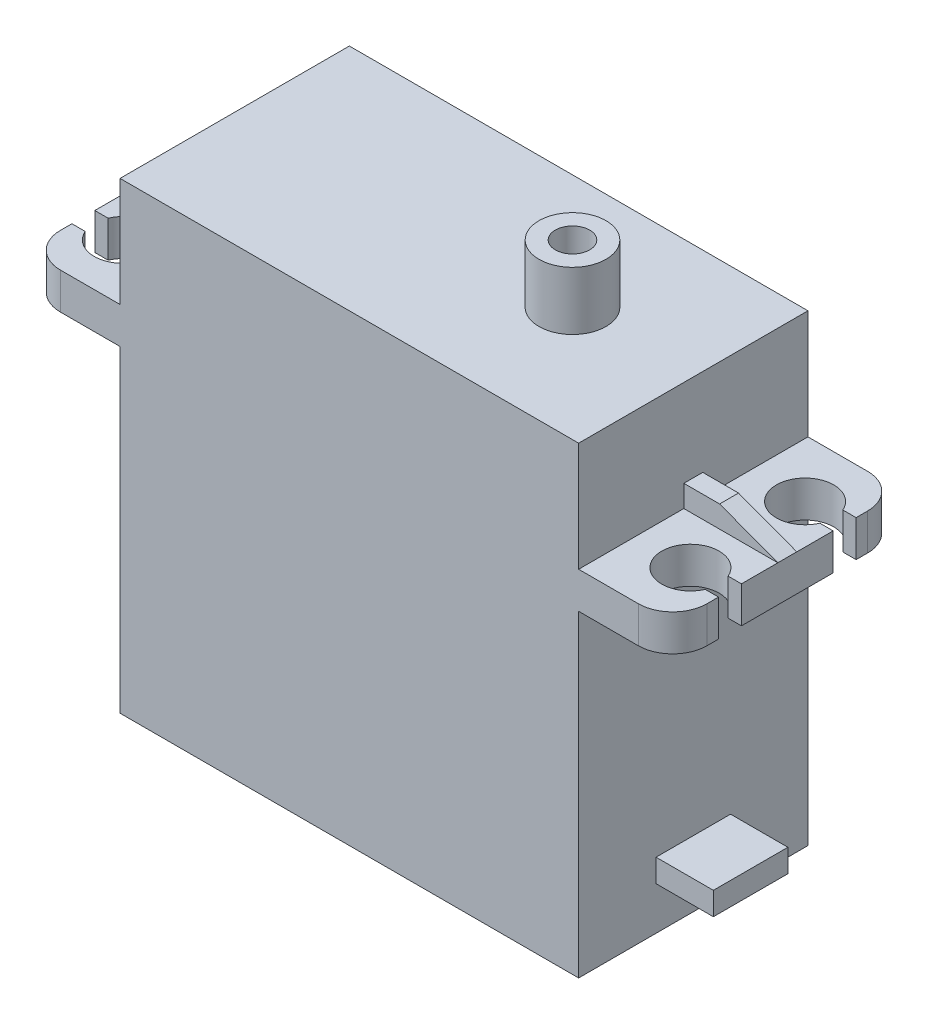
SolidWorks part; units mm, degrees
ref_plane "Front Plane" through (0, 0, 0) normal (0, 0, 1) x (1, 0, 0)
ref_plane "Top Plane" through (0, 0, 0) normal (0, 1, 0) x (1, 0, 0)
ref_plane "Right Plane" through (0, 0, 0) normal (1, 0, 0) x (0, 0, -1)
ref_plane "Plane1" through (0, 27.7, 0) normal (0, 1, 0) x (1, 0, 0)
sketch "Sketch1" plane through (0, 0, 0) normal (0, 1, 0) x (1, 0, 0)
  line L1 (-20, 10) -> (20, 10)
  line L2 (-20, 10) -> (-20, -10)
  line L3 (-20, -10) -> (20, -10)
  line L4 (20, 10) -> (20, -10)
  line L5 (-20, 10) -> (20, -10) construction
  line L6 (-20, -10) -> (20, 10) construction
  point P0 (0, 0)
  dimension "D1" = 40
  dimension "D2" = 20
extrude "Boss-Extrude1" add sketch "Sketch1" along normal blind 40.4
sketch "Sketch2" plane through (0, 27.7, 0) normal (0, 1, 0) x (1, 0, 0)
  line L1 (-28.2, 10) -> (28.2, 10)
  line L2 (-28.2, 10) -> (-28.2, -10)
  line L3 (-28.2, -10) -> (28.2, -10)
  line L4 (28.2, 10) -> (28.2, -10)
  line L5 (-28.2, 10) -> (28.2, -10) construction
  line L6 (-28.2, -10) -> (28.2, 10) construction
  point P0 (0, 0)
  dimension "D1" = 56.4
  dimension "D2" = 20
extrude "Boss-Extrude2" add sketch "Sketch2" along normal blind 3.175
sketch "Sketch3" plane through (0, 30.875, 0) normal (0, 1, 0) x (1, 0, 0)
  line L0 (-28.2, 0) -> (28.2, 0) construction
  line L1 (-24.75, -5) -> (24.75, -5) construction
  line L2 (-24.75, -5) -> (-24.75, 5) construction
  line L3 (-24.75, 5) -> (24.75, 5) construction
  line L4 (24.75, -5) -> (24.75, 5) construction
  line L5 (-28.2, 10) -> (-28.2, -10) construction
  line L6 (28.2, -10) -> (28.2, 10) construction
  line L7 (0, 5) -> (0, -5) construction
  circle A0 centre (-24.75, 5) radius 2.5
  circle A1 centre (-24.75, -5) radius 2.5
  circle A2 centre (24.75, 5) radius 2.5
  circle A3 centre (24.75, -5) radius 2.5
  point P6 (-24.75, 0)
  point P8 (24.75, 0)
  dimension "D3" = 5
  dimension "D1" = 10
  dimension "D2" = 49.5
extrude "Cut-Extrude1" cut sketch "Sketch3" against normal up to next
sketch "Sketch4" plane through (0, 30.875, 0) normal (0, 1, 0) x (1, 0, 0)
  line L0 (-24.75, -5) -> (-28.2, -5) construction
  line L1 (-28.2, 10) -> (-28.2, -10) construction
  line L2 (-27.0413, -4) -> (-28.2, -4)
  line L3 (-27.0413, -6) -> (-28.2, -6)
  line L4 (-28.2, -4) -> (-28.2, -6)
  line L5 (-24.75, -4) -> (-28.2, -4) construction
  line L6 (-24.75, -6) -> (-28.2, -6) construction
  circle A0 centre (-24.75, -5) radius 2.5 construction
  arc A1 (-27.0413, -4) -> (-27.0413, -6) centre (-24.75, -5) ccw
  dimension "D1" = 1
  dimension "D2" = 1
extrude "Cut-Extrude2" cut sketch "Sketch4" against normal up to next
mirror "Mirror1" about plane through (0, 0, 0) normal (1, 0, 0) of "Cut-Extrude2"
mirror "Mirror2" about plane through (0, 0, 0) normal (0, 0, 1) of "Cut-Extrude2", "Mirror1"
fillet "Fillet1" radius 3 4 edges at (28.2, 29.2875, -10) (28.2, 29.2875, 10) (-28.2, 29.2875, 10) (-28.2, 29.2875, -10)
sketch "Sketch5" plane through (20, 0, 0) normal (1, 0, 0) x (0, 0, -1)
  line L0 (0, 0) -> (0, 5.75) construction
  line L1 (-3.25, 5.75) -> (3.25, 5.75)
  line L2 (-3.25, 5.75) -> (-3.25, 3.75)
  line L3 (-3.25, 3.75) -> (3.25, 3.75)
  line L4 (3.25, 5.75) -> (3.25, 3.75)
  line L5 (-10, 0) -> (10, 0) construction
  dimension "D1" = 2
  dimension "D2" = 6.5
  dimension "D3" = 3.75
extrude "Boss-Extrude3" add sketch "Sketch5" along normal blind 5
sketch "Sketch6" plane through (0, 40.4, 0) normal (0, 1, 0) x (1, 0, 0)
  line L0 (-20, 0) -> (9.464, 0) construction
  line L1 (-20, 10) -> (-20, -10) construction
  circle A0 centre (9.464, 0) radius 2.921
  dimension "D2" = 5.842
  dimension "D1" = 29.464
extrude "Boss-Extrude4" add sketch "Sketch6" along normal blind 5.08
sketch "Sketch7" plane through (0, 30.875, 0) normal (0, 1, 0) x (1, 0, 0)
  line L0 (20, -10) -> (20, 10) construction
  line L1 (20, 0.8255) -> (28.2, 0.8255)
  line L2 (20, 0.8255) -> (20, -0.8255)
  line L3 (20, -0.8255) -> (28.2, -0.8255)
  line L4 (28.2, 0.8255) -> (28.2, -0.8255)
  line L5 (28.2, -4) -> (28.2, 4) construction
  line L6 (20, 0) -> (28.2, 0) construction
  dimension "D1" = 1.651
extrude "Boss-Extrude5" add sketch "Sketch7" along normal offset from surface (1.905 mm away) 5.08 up to face at (25.6732, 27.7, 0)
chamfer "Chamfer1" distance 1.9 distance2 5.08 1 edges at (28.2, 32.78, 0)
mirror "Mirror3" about plane through (0, 0, 0) normal (1, 0, 0) of "Boss-Extrude5"
chamfer "Chamfer2" distance 5.08 distance2 1.9 1 edges at (-28.2, 32.78, 0)
sketch "Sketch8" plane through (0, 45.48, 0) normal (0, 1, 0) x (1, 0, 0)
  circle A0 centre (9.464, 0) radius 1.5
  dimension "D1" = 3
extrude "Cut-Extrude3" cut sketch "Sketch8" against normal blind 9.25
